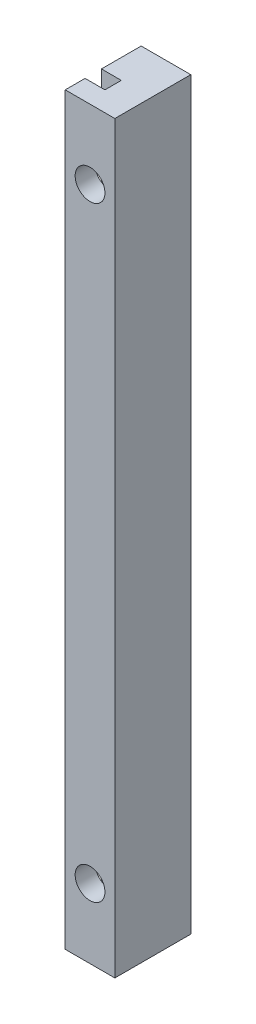
SolidWorks part; units mm, degrees
ref_plane "Front Plane" through (0, 0, 0) normal (0, 0, 1) x (1, 0, 0)
ref_plane "Top Plane" through (0, 0, 0) normal (0, 1, 0) x (1, 0, 0)
ref_plane "Right Plane" through (0, 0, 0) normal (1, 0, 0) x (0, 0, -1)
sketch "Sketch1" plane through (0, 0, 0) normal (0, 0, 1) x (1, 0, 0)
  line L0 (-26, -80) -> (-94, -80) construction
  line L1 (-26, -5) -> (-31, -5)
  line L2 (-26, -5) -> (-26, -80)
  line L3 (-26, -80) -> (-31, -80)
  line L4 (-31, -5) -> (-31, -80)
  dimension "D1" = 5
extrude "Boss-Extrude1" add sketch "Sketch1" along normal blind 4
sketch "Sketch2" plane through (0, 0, 4) normal (0, 0, 1) x (1, 0, 0)
  line L0 (-31, -80) -> (-26, -80) construction
  line L1 (-26, -5) -> (-29, -5)
  line L2 (-26, -5) -> (-26, -80)
  line L3 (-26, -80) -> (-29, -80)
  line L4 (-29, -5) -> (-29, -80)
  dimension "D1" = 3
extrude "Boss-Extrude2" add sketch "Sketch2" along normal blind 1.65
sketch "Sketch3" plane through (0, 0, 5.65) normal (0, 0, 1) x (1, 0, 0)
  line L0 (-31, -5) -> (-31, -80) construction
  line L1 (-26, -5) -> (-31, -5)
  line L2 (-26, -5) -> (-26, -80)
  line L3 (-26, -80) -> (-31, -80)
  line L4 (-31, -5) -> (-31, -80)
  line L5 (-31, -80) -> (-29, -80) construction
extrude "Boss-Extrude3" add sketch "Sketch3" along normal blind 2
sketch "Sketch4" plane through (0, 0, 7.65) normal (0, 0, 1) x (1, 0, 0)
  line L0 (-31, -80) -> (-26, -80) construction
  line L1 (-26, -5) -> (-31, -5) construction
  circle A0 centre (-28.5, -73) radius 1.5
  circle A1 centre (-28.5, -12) radius 1.5
  point P6 (-28.5, -80)
  dimension "D1" = 3
  dimension "D2" = 7
  dimension "D3" = 7
extrude "Cut-Extrude1" cut sketch "Sketch4" against normal through all
